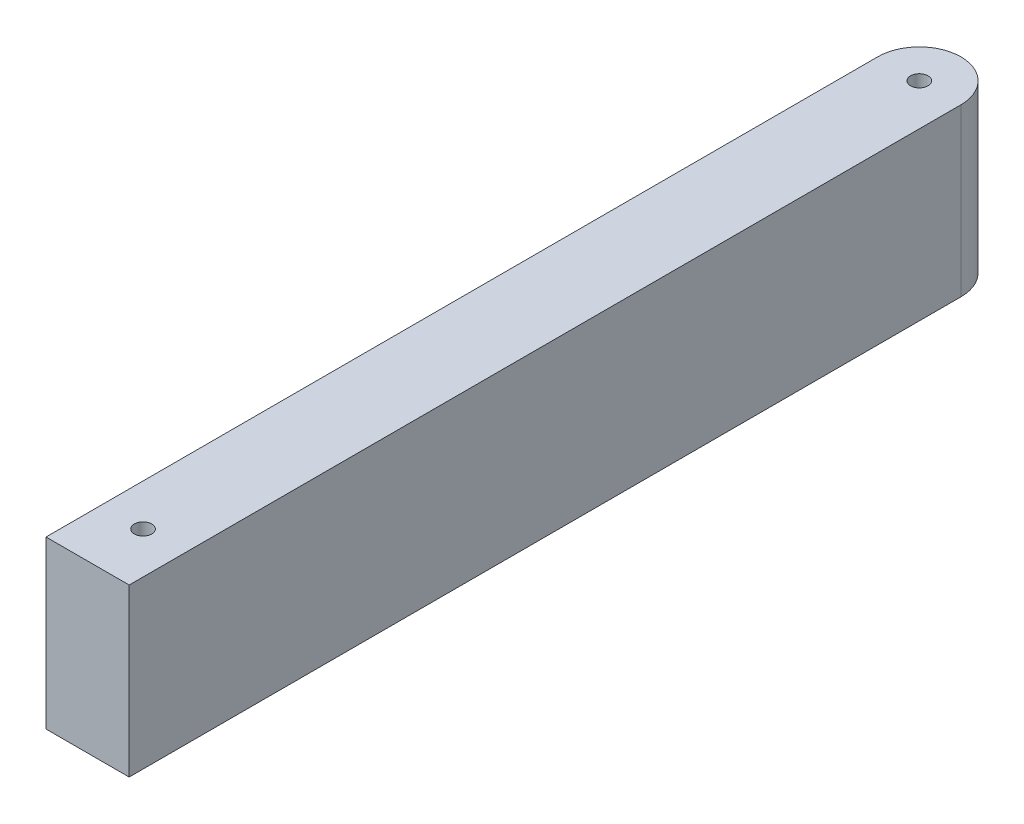
SolidWorks part; units mm, degrees
ref_plane "Front Plane" through (0, 0, 0) normal (0, 0, 1) x (1, 0, 0)
ref_plane "Top Plane" through (0, 0, 0) normal (0, 1, 0) x (1, 0, 0)
ref_plane "Right Plane" through (0, 0, 0) normal (1, 0, 0) x (0, 0, -1)
sketch "Sketch1" plane through (0, 0, 0) normal (0, 0, 1) x (1, 0, 0)
  line L0 (0, 0) -> (19.05, 0)
  line L1 (19.05, 0) -> (19.05, -76.2)
  line L2 (19.05, -76.2) -> (0, -76.2)
  line L3 (0, -76.2) -> (0, 0)
  dimension "D1" = 76.2
  dimension "D2" = 19.05
revolve "Revolve1" add sketch "Sketch1" angle 180 about L1
sketch "Sketch2" plane through (0, 0, 0) normal (0, 0, 1) x (1, 0, 0)
  line L1 (0, 0) -> (38.1, 0)
  line L2 (0, 0) -> (0, -76.2)
  line L3 (0, -76.2) -> (38.1, -76.2)
  line L4 (38.1, 0) -> (38.1, -76.2)
extrude "Boss-Extrude1" add sketch "Sketch2" along normal blind 381
sketch "Sketch3" plane through (0, 0, 0) normal (0, 1, 0) x (1, 0, 0)
  line L0 (38.1, 0) -> (0, 0) construction
  arc A0 (38.1, 0) -> (0, 0) centre (19.05, 0) ccw construction
  circle A1 centre (19.05, 0) radius 3.9878
  dimension "D1" = 7.9756
extrude "Cut-Extrude1" cut sketch "Sketch3" against normal through all
sketch "Sketch4" plane through (0, 0, 0) normal (0, 1, 0) x (1, 0, 0)
  line L0 (0, -437.3739) -> (38.1, -437.3739) construction
  line L1 (0, -381) -> (0, 0) construction
  line L2 (38.1, -381) -> (38.1, 0) construction
  line L3 (38.1, -381) -> (0, -381) construction
  line L4 (19.05, -381) -> (19.05, -330.2) construction
  circle A0 centre (19.05, -355.6) radius 3.9878
  point P14 (19.05, -355.6)
  dimension "D1" = 7.9756
  dimension "D2" = 25.4
extrude "Cut-Extrude2" cut sketch "Sketch4" against normal through all contours A0
